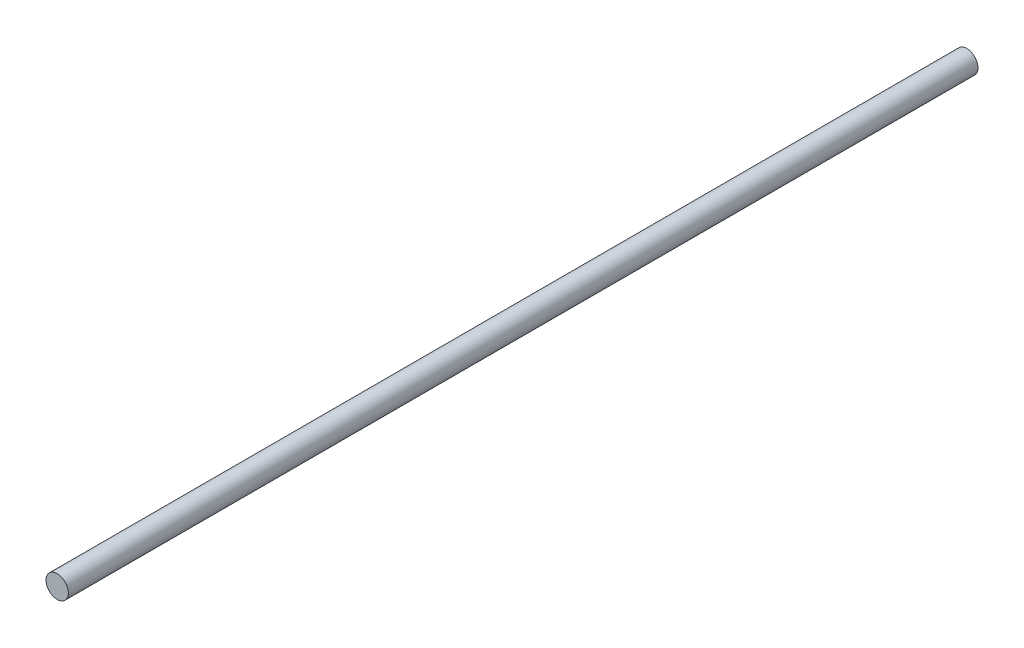
SolidWorks part; units mm, degrees
ref_plane "Front Plane" through (0, 0, 0) normal (0, 0, 1) x (1, 0, 0)
ref_plane "Top Plane" through (0, 0, 0) normal (0, 1, 0) x (1, 0, 0)
ref_plane "Right Plane" through (0, 0, 0) normal (1, 0, 0) x (0, 0, -1)
sketch "Sketch1" plane through (0, 0, 0) normal (0, 0, 1) x (1, 0, 0)
  circle A0 centre (0, 0) radius 50.8
  dimension "D1" = 101.6
extrude "Boss-Extrude1" add sketch "Sketch1" along normal blind 4133.088 contours A0
